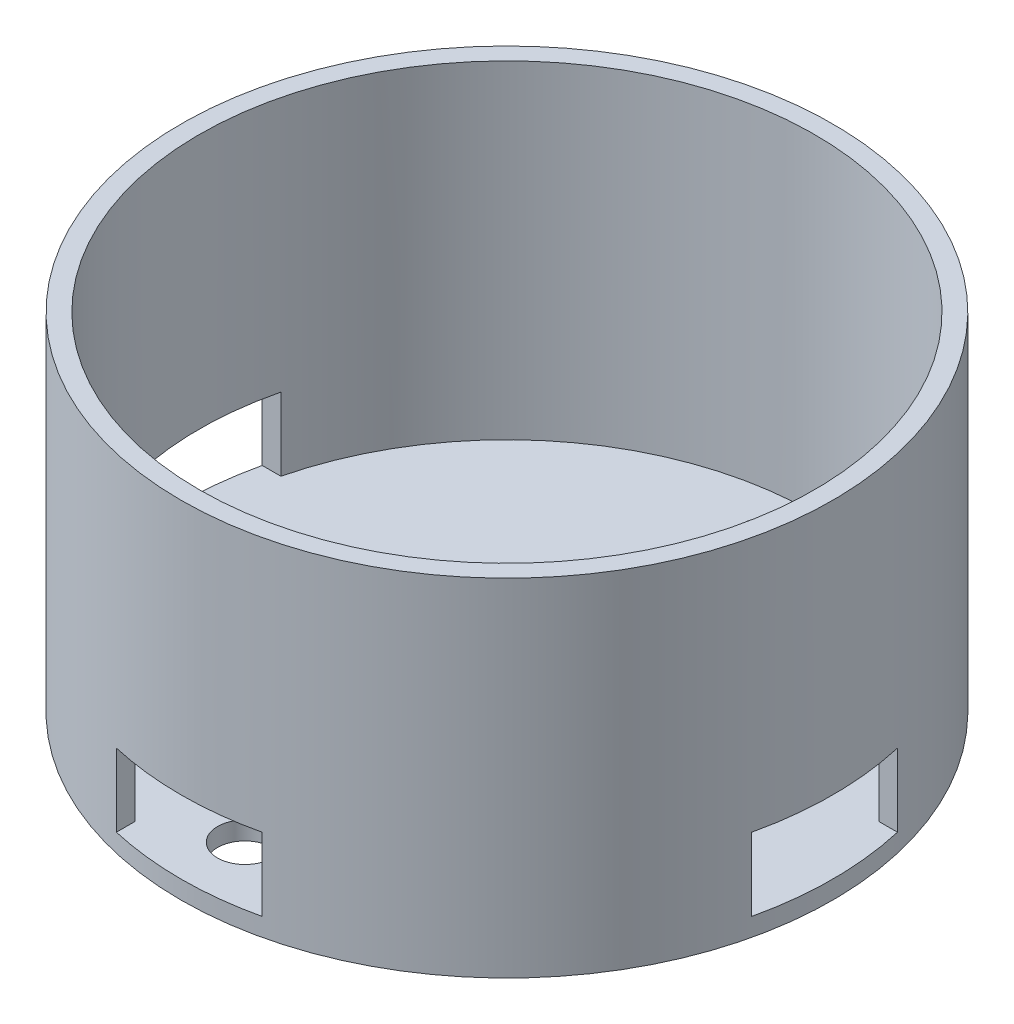
SolidWorks part; units mm, degrees
ref_plane "Front Plane" through (0, 0, 0) normal (0, 0, 1) x (1, 0, 0)
ref_plane "Top Plane" through (0, 0, 0) normal (0, 1, 0) x (1, 0, 0)
ref_plane "Right Plane" through (0, 0, 0) normal (1, 0, 0) x (0, 0, -1)
sketch "Sketch1" plane through (0, 0, 0) normal (0, 1, 0) x (1, 0, 0)
  circle A0 centre (0, 0) radius 56.769
  dimension "D1" = 113.538
extrude "Boss-Extrude1" add sketch "Sketch1" along normal blind 3.175
sketch "Sketch2" plane through (0, 3.175, 0) normal (0, 1, 0) x (1, 0, 0)
  circle A0 centre (0, 0) radius 56.769 construction
  circle A1 centre (0, 0) radius 56.769
  circle A2 centre (0, 0) radius 53.594
  dimension "D1" = 3.175
extrude "Boss-Extrude2" add sketch "Sketch2" along normal blind 57.15
sketch "Sketch3" plane through (0, 0, 0) normal (1, 0, 0) x (0, 0, -1)
  line L0 (53.594, 3.175) -> (-53.594, 3.175) construction
  line L1 (-12.7, 3.175) -> (12.7, 3.175)
  line L2 (-12.7, 3.175) -> (-12.7, 15.875)
  line L3 (-12.7, 15.875) -> (12.7, 15.875)
  line L4 (12.7, 3.175) -> (12.7, 15.875)
  line L5 (-12.7, 3.175) -> (12.7, 15.875) construction
  line L6 (-12.7, 15.875) -> (12.7, 3.175) construction
  point P0 (0, 9.525)
  point P7 (0, 0)
  dimension "D1" = 25.4
  dimension "D2" = 12.7
extrude "Cut-Extrude1" cut sketch "Sketch3" against normal through all
pattern_circular "CirPattern1" count 3 every 90 about axis through (0, 0, 0) along (0, 1, 0) of "Cut-Extrude1"
sketch "Sketch4" plane through (0, 3.175, 0) normal (0, 1, 0) x (1, 0, 0)
  line L0 (0, 45.6406) -> (0, 27.3844) construction
  line L1 (0, 27.3844) -> (0, 9.1281) construction
  line L2 (0, 9.1281) -> (0, -9.1281) construction
  line L3 (0, -9.1281) -> (0, -27.3844) construction
  line L4 (0, -27.3844) -> (0, -45.6406) construction
  circle A0 centre (0, 45.6406) radius 4.7625
  circle A1 centre (0, 27.3844) radius 4.7625
  circle A2 centre (0, 9.1281) radius 4.7625
  circle A3 centre (0, -9.1281) radius 4.7625
  circle A4 centre (0, -27.3844) radius 4.7625
  circle A5 centre (0, -45.6406) radius 4.7625
  point P12 (0, 42.9625)
  point P14 (0, -10.1179)
  point P15 (0, 0)
  dimension "D1" = 9.525
  dimension "D2" = 18.2562
extrude "Cut-Extrude2" cut sketch "Sketch4" against normal through all
